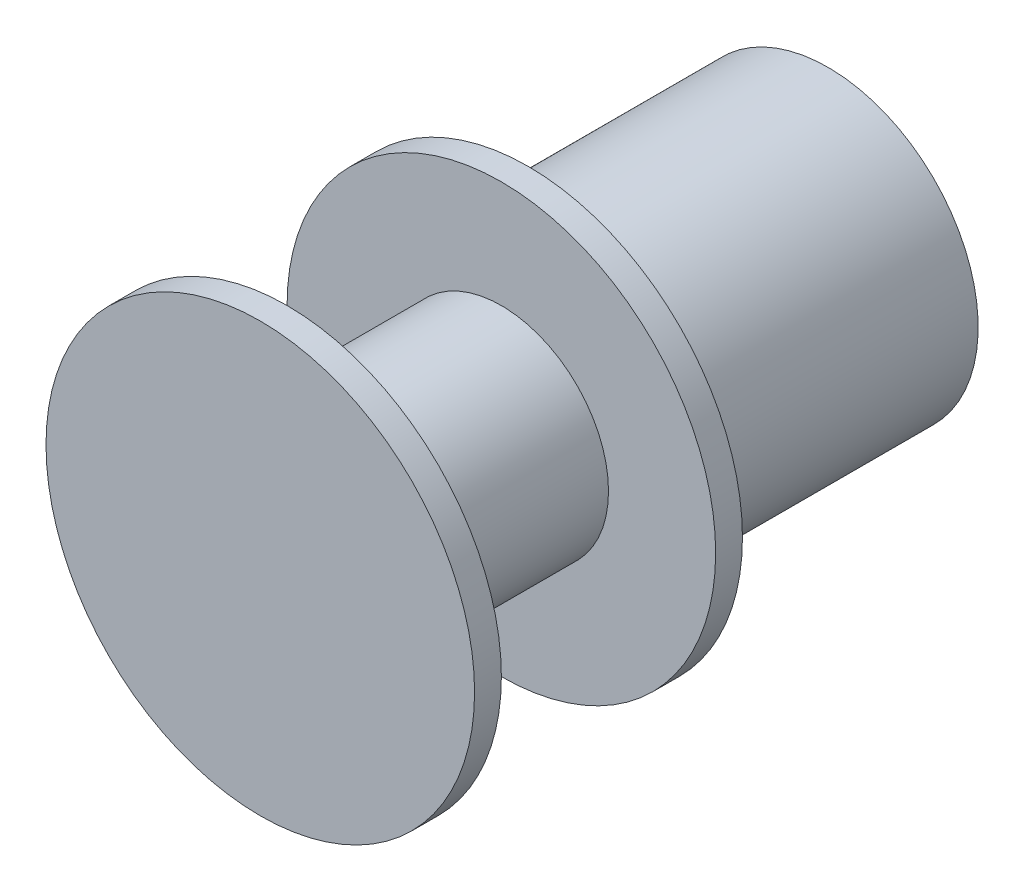
SolidWorks part; units mm, degrees
ref_plane "Front Plane" through (0, 0, 0) normal (0, 0, 1) x (1, 0, 0)
ref_plane "Top Plane" through (0, 0, 0) normal (0, 1, 0) x (1, 0, 0)
ref_plane "Right Plane" through (0, 0, 0) normal (1, 0, 0) x (0, 0, -1)
sketch "Sketch1" plane through (0, 0, 0) normal (0, 0, 1) x (1, 0, 0)
  circle A0 centre (0, 0) radius 6.35
  dimension "D1" = 12.7
extrude "Boss-Extrude1" add sketch "Sketch1" along normal blind 0.7937
sketch "Sketch2" plane through (0, 0, 0.7937) normal (0, 0, 1) x (1, 0, 0)
  circle A0 centre (0, 0) radius 3.175
  dimension "D1" = 6.35
extrude "Boss-Extrude2" add sketch "Sketch2" along normal blind 6.35
sketch "Sketch3" plane through (0, 0, 7.1437) normal (0, 0, 1) x (1, 0, 0)
  circle A0 centre (0, 0) radius 6.35
extrude "Boss-Extrude3" add sketch "Sketch3" along normal blind 0.7937
sketch "Sketch4" plane through (0, 0, 0) normal (0, 0, -1) x (-1, 0, 0)
  circle A0 centre (0, 0) radius 4.445
  dimension "D1" = 8.89
extrude "Boss-Extrude4" add sketch "Sketch4" along normal blind 8.89
sketch "Sketch5" plane through (0, 0, -8.89) normal (0, 0, -1) x (-1, 0, 0)
  circle A0 centre (0, 0) radius 3.175
  dimension "D1" = 6.35
extrude "Cut-Extrude1" cut sketch "Sketch5" against normal blind 3.175
